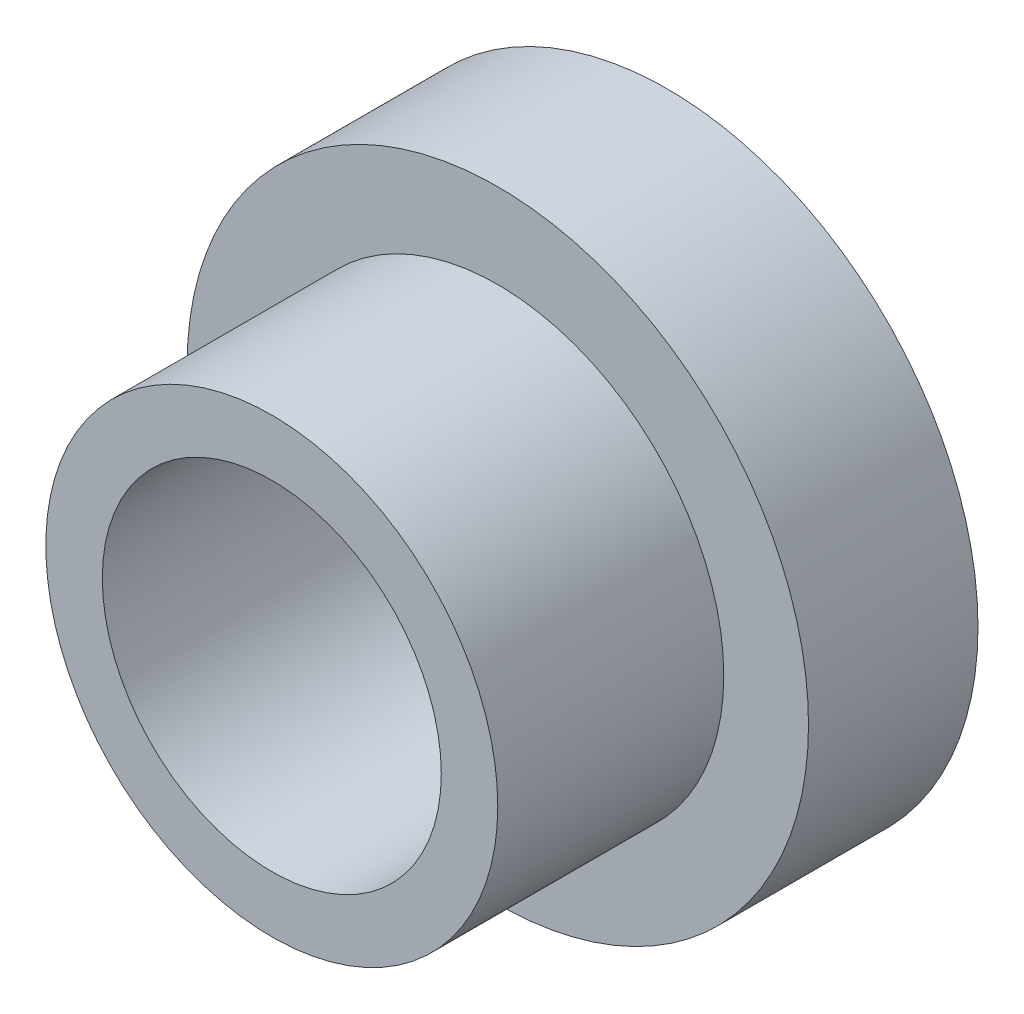
SolidWorks part; units mm, degrees
ref_plane "Спереди" through (0, 0, 0) normal (0, 0, 1) x (1, 0, 0)
ref_plane "Сверху" through (0, 0, 0) normal (0, 1, 0) x (1, 0, 0)
ref_plane "Справа" through (0, 0, 0) normal (1, 0, 0) x (0, 0, -1)
sketch "Эскиз1" plane through (0, 0, 0) normal (0, 0, 1) x (1, 0, 0)
  circle A0 centre (0, 0) radius 5.5
  dimension "D1" = 11
extrude "Основание-Вытянуть" add sketch "Эскиз1" along normal blind 3
sketch "Эскиз2" plane through (0, 0, 3) normal (0, 0, 1) x (1, 0, 0)
  circle A0 centre (0, 0) radius 4
  dimension "D1" = 8
extrude "Бобышка-Вытянуть1" add sketch "Эскиз2" along normal blind 4
sketch "Эскиз3" plane through (0, 0, 7) normal (0, 0, 1) x (1, 0, 0)
  circle A0 centre (0, 0) radius 3
  dimension "D1" = 6
extrude "Вырез-Вытянуть1" cut sketch "Эскиз3" against normal through all
